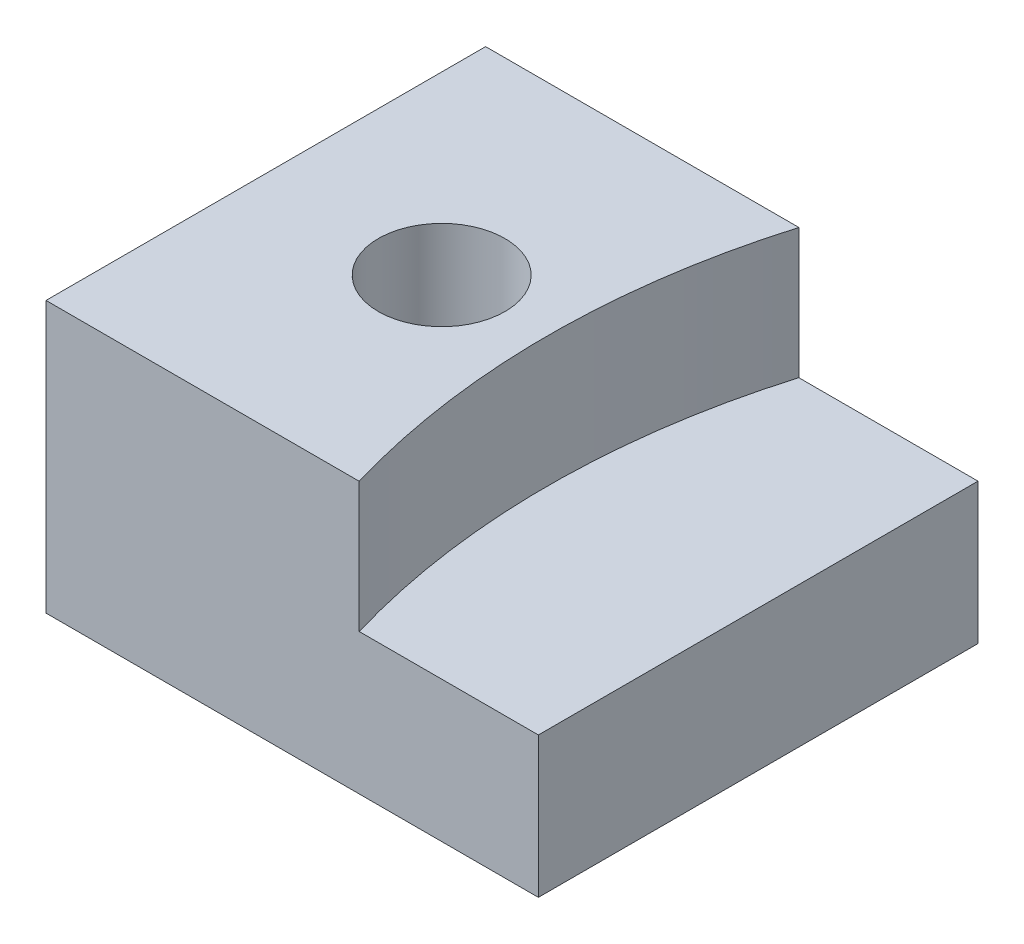
SolidWorks part; units mm, degrees
material "Delrin 2700 NC010, Low Viscosity Acetal Copolymer (SS)"
ref_plane "Front" through (0, 0, 0) normal (0, 0, 1) x (1, 0, 0)
ref_plane "Top" through (0, 0, 0) normal (0, 1, 0) x (1, 0, 0)
ref_plane "Right" through (0, 0, 0) normal (1, 0, 0) x (0, 0, -1)
sketch "Sketch3" plane through (0, 0, 0) normal (0, 1, 0) x (1, 0, 0)
  line L5 (-2.5, -3.125) -> (4.5, -3.125)
  line L6 (-2.5, -3.125) -> (-2.5, 3.125)
  line L7 (-2.5, 3.125) -> (4.5, 3.125)
  line L8 (4.5, -3.125) -> (4.5, 3.125)
  circle A0 centre (0, 0) radius 0.9
  point P9 (-2.5, 0)
  dimension "D1" = 1.8
  dimension "D2" = 6.25
  dimension "D3" = 2.5
  dimension "D4" = 7
extrude "Boss-Extrude1" add sketch "Sketch3" along normal blind 2
sketch "Sketch6" plane through (0, 2, 0) normal (0, 1, 0) x (1, 0, 0)
  line L0 (-2.5, 3.125) -> (-2.5, -3.125) construction
  line L1 (-2.5, 3.125) -> (-2.5, -3.125)
  line L2 (-2.5, 3.125) -> (1.9532, 3.125)
  line L3 (4.5, 3.125) -> (-2.5, 3.125) construction
  line L4 (1.9532, 3.125) -> (1.9532, -3.125) construction
  line L5 (-2.5, -3.125) -> (4.5, -3.125) construction
  line L6 (1.9532, -3.125) -> (-2.5, -3.125)
  circle A0 centre (0, 0) radius 0.9 construction
  circle A1 centre (0, 0) radius 0.9
  arc A2 (1.9532, -3.125) -> (1.9532, 3.125) centre (12.5, 0) cw
  point P12 (1.5, 0)
  dimension "D1" = 11
  dimension "D2" = 1.5
extrude "Boss-Extrude3" add sketch "Sketch6" along normal blind 1.85
